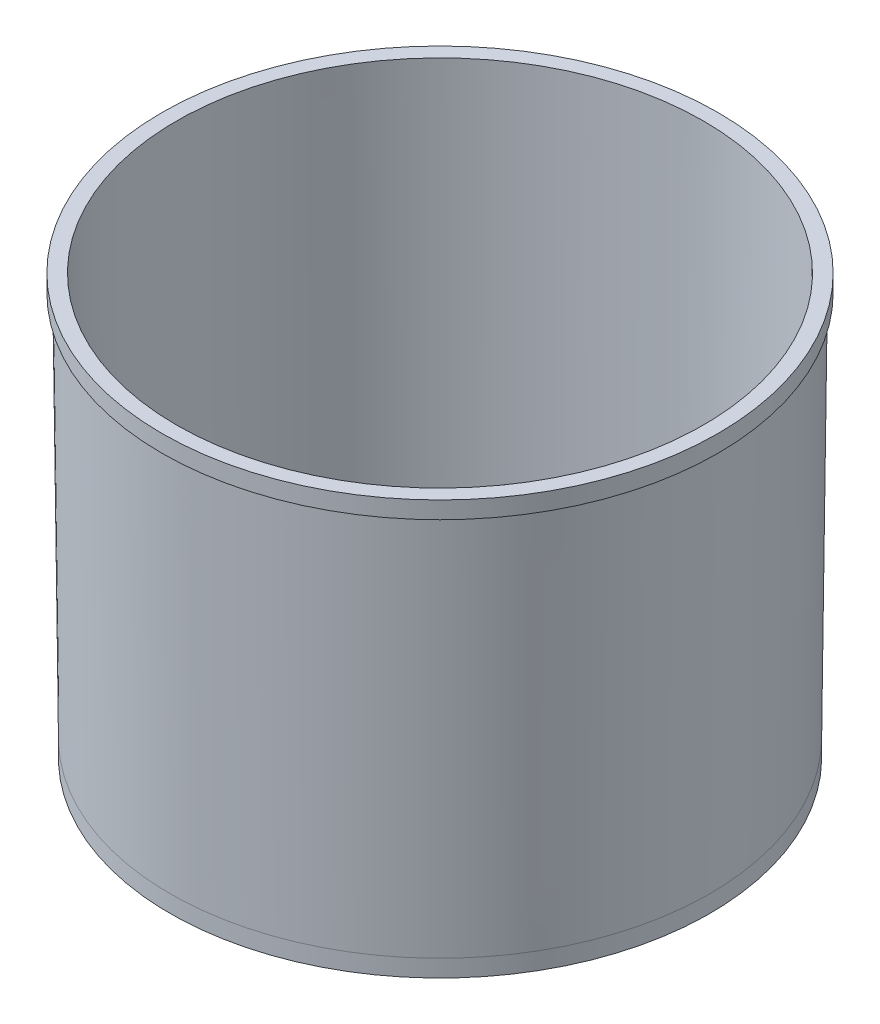
SolidWorks part; units mm, degrees
ref_plane "前视基准面" through (0, 0, 0) normal (0, 0, 1) x (1, 0, 0)
ref_plane "上视基准面" through (0, 0, 0) normal (0, 1, 0) x (1, 0, 0)
ref_plane "右视基准面" through (0, 0, 0) normal (1, 0, 0) x (0, 0, -1)
ref_axis "基准轴1" through (0, -2.4, 0) along (0, 1, 0)
ref_plane "基准面1" through (0, 47, 0) normal (0, 1, 0) x (1, 0, 0)
sketch "草图1" plane through (0, 0, 0) normal (0, 0, 1) x (1, 0, 0)
  line L1 (55, 47) -> (-55, 47) construction
  line L2 (-31.9788, 45) -> (-31.5, 0)
  line L3 (55, 0) -> (-55, 0) construction
  line L4 (-31.5, 0) -> (-30.2499, 0)
  line L5 (-30.2499, 0) -> (-30.75, 47)
  line L6 (0, -55) -> (0, 55) construction
  line L8 (-32.45, 47) -> (-32.45, 45)
  line L9 (-32.45, 45) -> (-31.9788, 45)
  line L10 (-30.75, 47) -> (-32.45, 47)
  dimension "D1" = 1.25
  dimension "D2" = 30.75
  dimension "D3" = 31.5
  dimension "D4" = 2
  dimension "D5" = 32.45
revolve "旋转1" add sketch "草图1" angle 360 about axis through (0, -2.4, 0) along (0, 1, 0)
sketch "草图2" plane through (0, 0, 0) normal (0, -1, 0) x (1, 0, 0)
  circle A0 centre (0, 0) radius 30.2499 construction
  circle A1 centre (0, 0) radius 31.5
  circle A2 centre (0, 0) radius 31.5
  circle A3 centre (0, 0) radius 30.2499
  dimension "D1" = 0
extrude "凸台-拉伸1" add sketch "草图2" along normal blind 2
